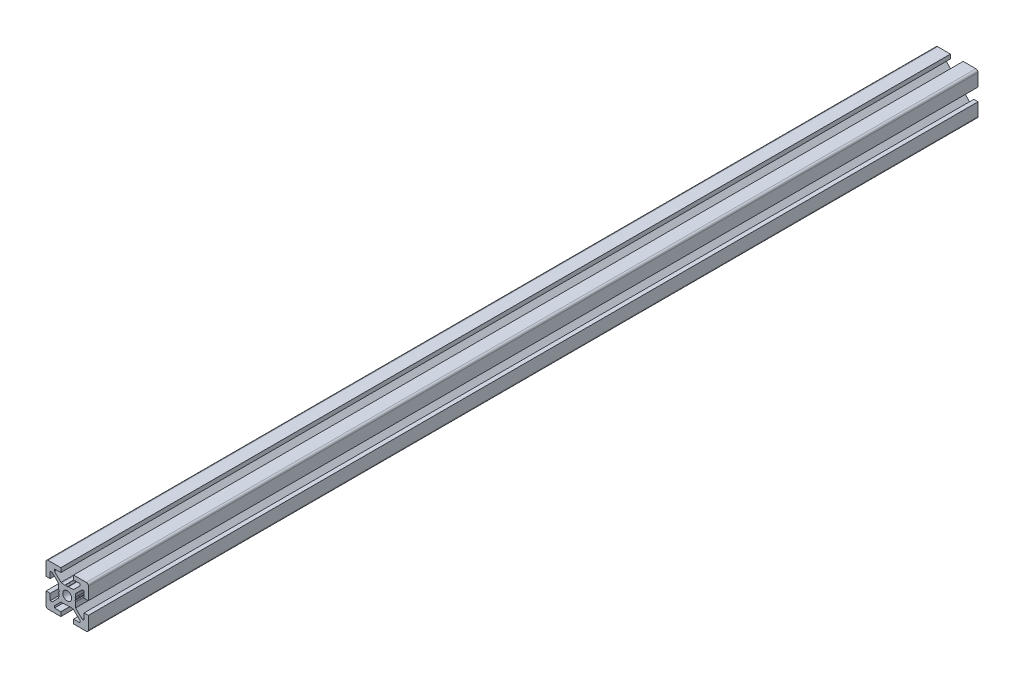
SolidWorks part; units mm, degrees
ref_plane "Front Plane" through (0, 0, 0) normal (0, 0, 1) x (1, 0, 0)
ref_plane "Top Plane" through (0, 0, 0) normal (0, 1, 0) x (1, 0, 0)
ref_plane "Right Plane" through (0, 0, 0) normal (1, 0, 0) x (0, 0, -1)
ref_plane "Plane1" through (0, 0, -2000) normal (0, 0, -1) x (-1, 0, 0)
sketch "Sketch1" plane through (0, 0, -2000) normal (0, 0, -1) x (-1, 0, 0)
  line L0 (10, -3) -> (8, -3)
  line L1 (8, -3) -> (8, -6)
  line L2 (8, -6) -> (7.0607, -6)
  line L3 (7.0607, -6) -> (4, -2.9393)
  line L4 (4, -2.9393) -> (4, -2.5)
  line L5 (4, -2.5) -> (3.751, -1.2189)
  line L6 (3.751, -1.2189) -> (3.933, -0.9036)
  line L7 (3.933, -0.4036) -> (3.7, 0)
  line L8 (3.7, 0) -> (3.933, 0.4036)
  line L9 (4, 0.6536) -> (4, 2.9393)
  line L10 (4, 2.9393) -> (7.0607, 6)
  line L11 (7.0607, 6) -> (8, 6)
  line L12 (8, 6) -> (8, 3)
  line L13 (8, 3) -> (10, 3)
  line L14 (10, 3) -> (10, 9)
  line L15 (9, 10) -> (3, 10)
  line L16 (3, 10) -> (3, 8)
  line L17 (3, 8) -> (6, 8)
  line L18 (6, 8) -> (6, 7.0607)
  line L19 (6, 7.0607) -> (2.9393, 4)
  line L20 (2.9393, 4) -> (2.5, 4)
  line L21 (2.5, 4) -> (1.2189, 3.751)
  line L22 (1.2189, 3.751) -> (0.9036, 3.933)
  line L23 (0.4036, 3.933) -> (0, 3.7)
  line L24 (0, 3.7) -> (-0.4036, 3.933)
  line L25 (-0.6536, 4) -> (-2.9393, 4)
  line L26 (-2.9393, 4) -> (-6, 7.0607)
  line L27 (-6, 7.0607) -> (-6, 8)
  line L28 (-6, 8) -> (-3, 8)
  line L29 (-3, 8) -> (-3, 10)
  line L30 (-3, 10) -> (-9, 10)
  line L31 (-10, 9) -> (-10, 3)
  line L32 (-10, 3) -> (-8, 3)
  line L33 (-8, 3) -> (-8, 6)
  line L34 (-8, 6) -> (-7.0607, 6)
  line L35 (-7.0607, 6) -> (-4, 2.9393)
  line L36 (-4, 2.9393) -> (-4, 2.5)
  line L37 (-4, 2.5) -> (-3.751, 1.2189)
  line L38 (-3.751, 1.2189) -> (-3.933, 0.9036)
  line L39 (-3.933, 0.4036) -> (-3.7, 0)
  line L40 (-3.7, 0) -> (-3.933, -0.4036)
  line L41 (-4, -0.6536) -> (-4, -2.9393)
  line L42 (-4, -2.9393) -> (-7.0607, -6)
  line L43 (-7.0607, -6) -> (-8, -6)
  line L44 (-8, -6) -> (-8, -3)
  line L45 (-8, -3) -> (-10, -3)
  line L46 (-10, -3) -> (-10, -9)
  line L47 (-9, -10) -> (-3, -10)
  line L48 (-3, -10) -> (-3, -8)
  line L49 (-3, -8) -> (-6, -8)
  line L50 (-6, -8) -> (-6, -7.0607)
  line L51 (-6, -7.0607) -> (-2.9393, -4)
  line L52 (-2.9393, -4) -> (-2.5, -4)
  line L53 (-2.5, -4) -> (-1.2189, -3.751)
  line L54 (-1.2189, -3.751) -> (-0.9036, -3.933)
  line L55 (-0.4036, -3.933) -> (0, -3.7)
  line L56 (0, -3.7) -> (0.4036, -3.933)
  line L57 (0.6536, -4) -> (2.9393, -4)
  line L58 (2.9393, -4) -> (6, -7.0607)
  line L59 (6, -7.0607) -> (6, -8)
  line L60 (6, -8) -> (3, -8)
  line L61 (3, -8) -> (3, -10)
  line L62 (3, -10) -> (9, -10)
  line L63 (10, -9) -> (10, -3)
  circle A0 centre (0, 0) radius 2.1
  arc A1 (3.933, -0.9036) -> (3.933, -0.4036) centre (3.5, -0.6536) ccw
  arc A2 (3.933, 0.4036) -> (4, 0.6536) centre (3.5, 0.6536) ccw
  arc A3 (10, 9) -> (9, 10) centre (9, 9) ccw
  arc A4 (0.9036, 3.933) -> (0.4036, 3.933) centre (0.6536, 3.5) ccw
  arc A5 (-0.4036, 3.933) -> (-0.6536, 4) centre (-0.6536, 3.5) ccw
  arc A6 (-9, 10) -> (-10, 9) centre (-9, 9) ccw
  arc A7 (-3.933, 0.9036) -> (-3.933, 0.4036) centre (-3.5, 0.6536) ccw
  arc A8 (-3.933, -0.4036) -> (-4, -0.6536) centre (-3.5, -0.6536) ccw
  arc A9 (-10, -9) -> (-9, -10) centre (-9, -9) ccw
  arc A10 (-0.9036, -3.933) -> (-0.4036, -3.933) centre (-0.6536, -3.5) ccw
  arc A11 (0.4036, -3.933) -> (0.6536, -4) centre (0.6536, -3.5) ccw
  arc A12 (9, -10) -> (10, -9) centre (9, -9) ccw
extrude "Boss-Extrude1" add sketch "Sketch1" against normal blind 420
